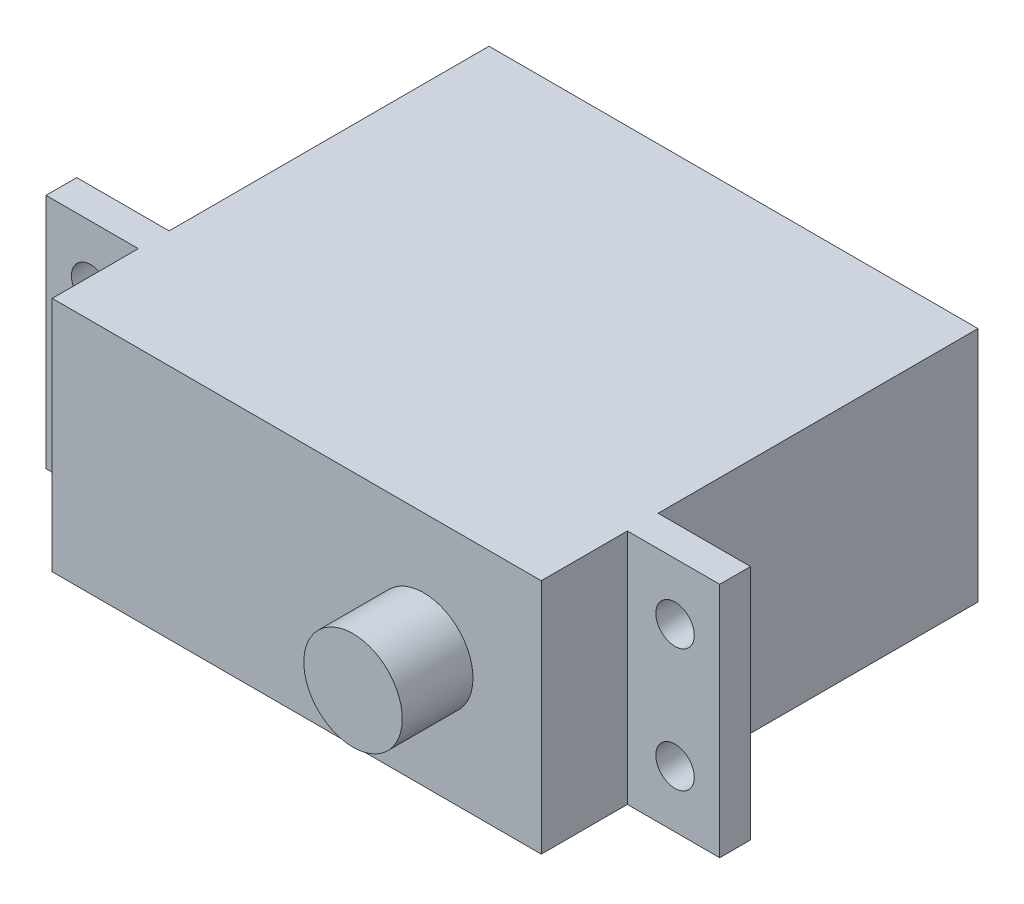
SolidWorks part; units mm, degrees
ref_plane "Front Plane" through (0, 0, 0) normal (0, 0, 1) x (1, 0, 0)
ref_plane "Top Plane" through (0, 0, 0) normal (0, 1, 0) x (1, 0, 0)
ref_plane "Right Plane" through (0, 0, 0) normal (1, 0, 0) x (0, 0, -1)
sketch "Sketch1" plane through (0, 0, 0) normal (0, 0, 1) x (1, 0, 0)
  line L0 (6750.0933, 3552.3471) -> (6750.0933, 3532.7891)
  line L1 (6750.0933, 3532.7891) -> (6790.4793, 3532.7891)
  line L2 (6790.4793, 3532.7891) -> (6790.4793, 3552.3471)
  line L3 (6790.4793, 3552.3471) -> (6750.0933, 3552.3471)
extrude "Boss-Extrude1" add sketch "Sketch1" along normal blind 36.068
ref_plane "Plane2" through (0, 0, 28.956) normal (0, 0, 1) x (1, 0, 0)
sketch "Sketch2" plane through (0, 0, 28.956) normal (0, 0, 1) x (1, 0, 0)
  line L0 (6790.4793, 3552.3471) -> (6798.1068, 3552.3471)
  line L1 (6798.1068, 3552.3471) -> (6798.1068, 3532.7891)
  line L2 (6798.1068, 3532.7891) -> (6790.4793, 3532.7891)
  line L3 (6790.4793, 3532.7891) -> (6790.4793, 3552.3471)
  line L4 (6750.0933, 3552.3471) -> (6742.4658, 3552.3471)
  line L5 (6742.4658, 3552.3471) -> (6742.4658, 3532.7891)
  line L6 (6742.4658, 3532.7891) -> (6750.0933, 3532.7891)
  line L7 (6750.0933, 3532.7891) -> (6750.0933, 3552.3471)
  circle A0 centre (6746.1563, 3547.6481) radius 1.5875
  circle A1 centre (6746.1563, 3537.4881) radius 1.5875
  circle A2 centre (6794.4163, 3537.4881) radius 1.5875
  circle A3 centre (6794.4163, 3547.6481) radius 1.5875
extrude "Boss-Extrude2" add sketch "Sketch2" against normal blind 2.54
sketch "Sketch3" plane through (0, 0, 36.068) normal (0, 0, 1) x (1, 0, 0)
  circle A0 centre (6780.7758, 3542.5681) radius 4.064
extrude "Boss-Extrude3" add sketch "Sketch3" along normal blind 5.842
